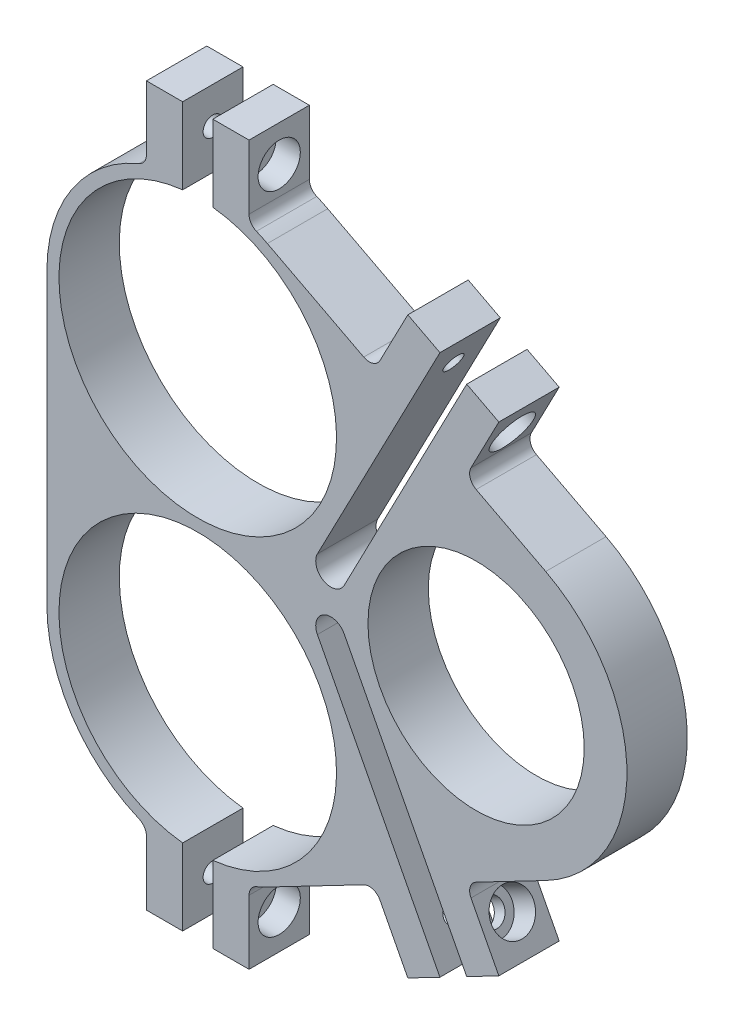
SolidWorks part; units mm, degrees
ref_plane "Front Plane" through (0, 0, 0) normal (0, 0, 1) x (1, 0, 0)
ref_plane "Top Plane" through (0, 0, 0) normal (0, 1, 0) x (1, 0, 0)
ref_plane "Right Plane" through (0, 0, 0) normal (1, 0, 0) x (0, 0, -1)
sketch "Sketch1" plane through (0, 0, 0) normal (0, 0, 1) x (1, 0, 0)
  line L0 (-39.6875, 76.2) -> (-39.6875, 0)
  line L1 (-39.6875, 38.1) -> (73.2318, 38.1) construction
  line L2 (18.3173, 111.4076) -> (46.4834, 96.7537)
  line L3 (3.9688, -36.2962) -> (3.9688, -56.3731)
  line L4 (0, 76.2) -> (0, 0) construction
  line L5 (-13.4938, -37.3231) -> (-13.4938, -56.3731)
  line L6 (3.9688, -56.3731) -> (13.4938, -56.3731)
  line L7 (-3.9688, -56.3731) -> (-13.4938, -56.3731)
  line L8 (13.4938, -37.3231) -> (13.4938, -56.3731)
  line L9 (-3.9687, -36.2962) -> (-3.9688, -56.3731)
  line L10 (18.3173, -35.2076) -> (46.4834, -20.5537)
  line L11 (13.4938, 113.5231) -> (13.4938, 132.5731)
  line L12 (-3.9688, 132.5731) -> (-13.4938, 132.5731)
  line L13 (3.9688, 132.5731) -> (13.4938, 132.5731)
  line L14 (3.9688, 132.5731) -> (3.9688, 112.4962)
  line L15 (-13.4938, 113.5231) -> (-13.4938, 132.5731)
  line L16 (54.9332, 92.3576) -> (61.9747, 88.6941) construction
  line L17 (54.9332, 92.3576) -> (31.487, 47.2919)
  line L18 (-3.9688, 132.5731) -> (-3.9688, 112.4962)
  line L19 (61.9747, 88.6941) -> (38.5286, 43.6284)
  line L20 (31.487, 47.2919) -> (38.5286, 43.6284) construction
  line L21 (54.9332, -16.1576) -> (31.487, 28.9081)
  line L22 (54.9332, 92.3576) -> (63.7255, 109.2572)
  line L23 (3.9688, 132.5731) -> (-3.9688, 132.5731) construction
  line L24 (46.4834, 96.7537) -> (55.2757, 113.6534)
  line L25 (3.9688, -56.3731) -> (-3.9688, -56.3731) construction
  line L26 (63.7255, 109.2572) -> (55.2757, 113.6534)
  line L27 (35.0078, 45.4601) -> (58.454, 90.5259) construction
  line L28 (61.9747, 88.6941) -> (70.767, 105.5938)
  line L29 (70.767, 105.5938) -> (79.2168, 101.1976)
  line L30 (70.4245, 84.298) -> (79.2168, 101.1976)
  line L31 (70.4245, 84.298) -> (91.5491, 73.3076)
  line L32 (61.9747, -12.4941) -> (38.5286, 32.5716)
  line L33 (70.4245, -8.098) -> (79.2168, -24.9976)
  line L34 (70.767, -29.3938) -> (79.2168, -24.9976)
  line L35 (61.9747, -12.4941) -> (70.767, -29.3938)
  line L36 (54.9332, -16.1576) -> (63.7255, -33.0572)
  line L37 (63.7255, -33.0572) -> (55.2757, -37.4534)
  line L38 (46.4834, -20.5537) -> (55.2757, -37.4534)
  line L39 (35.0078, 30.7399) -> (58.454, -14.3259) construction
  line L40 (54.9332, -16.1576) -> (61.9747, -12.4941) construction
  line L41 (70.4245, -8.098) -> (91.5491, 2.8924)
  arc A0 (3.9688, -36.2962) -> (-3.9687, -36.2962) centre (0, 0) ccw
  arc A1 (-3.9688, 112.4962) -> (3.9688, 112.4962) centre (0, 76.2) ccw
  arc A2 (13.4938, 113.5231) -> (18.3173, 111.4076) centre (0, 76.2) cw
  arc A3 (-39.6875, 0) -> (-13.4938, -37.3231) centre (0, 0) ccw
  circle A4 centre (73.2318, 38.1) radius 28.448
  arc A5 (13.4938, -37.3231) -> (18.3173, -35.2076) centre (0, 0) ccw
  arc A6 (-39.6875, 76.2) -> (-13.4938, 113.5231) centre (0, 76.2) cw
  circle A7 centre (73.2318, 38.1) radius 39.6875 construction
  circle A8 centre (0, 0) radius 36.5125 construction
  circle A9 centre (0, 76.2) radius 36.5125 construction
  circle A10 centre (0, 0) radius 39.6875 construction
  circle A11 centre (73.2318, 38.1) radius 36.5125 construction
  circle A12 centre (0, 76.2) radius 39.6875 construction
  arc A13 (91.5491, 73.3076) -> (91.5491, 2.8924) centre (73.2318, 38.1) cw
  circle A14 centre (35.0078, 45.4601) radius 3.9687 construction
  arc A15 (31.487, 47.2919) -> (38.5286, 43.6284) centre (35.0078, 45.4601) ccw
  circle A16 centre (35.0078, 30.7399) radius 3.9687 construction
  arc A17 (31.487, 28.9081) -> (38.5286, 32.5716) centre (35.0078, 30.7399) cw
  point P14 (0, 36.5125)
  point P51 (58.454, 90.5259)
  point P52 (0, 0)
  point P53 (0, 0)
  dimension "D2" = 56.896
  dimension "D4" = 73.025
  dimension "D5" = 73.025
  dimension "D7" = 79.375
  dimension "D9" = 79.375
  dimension "D10" = 73.025
  dimension "D11" = 7.9375
  dimension "D1" = 7.9375
  dimension "D3" = 76.2
  dimension "D6" = 9.525
  dimension "D8" = 19.05
  dimension "D12" = 82.55
  dimension "D13" = 41.275
  dimension "D14" = 50.8
  dimension "D15" = 19.05
  dimension "D16" = 9.525
extrude "Extrude1" add sketch "Sketch1" along normal mid plane 15.875
hole_wizard "CBORE for 1/4 Socket Head Cap Screw1" positions "Sketch3" profile "Sketch2" counterbore size "1/4" standard "Ansi Inch"
sketch "Sketch3" plane through (13.4938, 0, 0) normal (1, 0, 0) x (0, 0, -1)
  line L0 (7.9375, 132.5731) -> (-7.9375, 113.5231) construction
  point P0 (0, 123.0481)
sketch "Sketch2" plane through (13.4938, 123.0481, 0) normal (0, 1, 0) x (0, 0, -1)
  line L0 (0, 0) -> (0, 9.525)
  line L1 (0, 9.525) -> (3.3782, 9.525)
  line L3 (3.3782, 9.525) -> (3.3782, 6.35)
  line L4 (3.3782, 6.35) -> (5.5562, 6.35)
  line L5 (5.5562, 6.35) -> (5.5562, 0)
  line L7 (5.5562, 0) -> (0, 0)
  line L11 (0, -6.35) -> (0, 107.95) construction
  dimension "Thru Hole Dia." = 6.7564
  dimension "Thru Hole Depth" = 9.525
  dimension "C'Bore Dia." = 11.1125
  dimension "C'Bore Depth" = 6.35
hole_wizard "1/4-20 Tapped Hole1" positions "Sketch5" profile "Sketch4" tap size "1/4-20" standard "Ansi Inch" end condition through all
sketch "Sketch5" plane through (-3.9687, 0, 0) normal (1, 0, 0) x (0, 0, -1)
  point P0 (0, 123.0481)
sketch "Sketch4" plane through (-3.9688, 123.0481, 0) normal (0, 1, 0) x (0, 0, -1)
  line L0 (0, 0) -> (0, 35.7188)
  line L1 (0, 35.7188) -> (2.5527, 35.7188)
  line L2 (2.5527, 35.7188) -> (2.5527, 0)
  line L5 (2.5527, 0) -> (0, 0)
  line L11 (0, -6.35) -> (0, 107.95) construction
  dimension "Thru Tap Drill Dia." = 5.1054
  dimension "Thru Tap Drill Depth" = 35.7188
cosmetic thread "Hole Thread1" parameters "D2"=6.35
hole_wizard "CBORE for 1/4 Socket Head Cap Screw3" positions "Sketch16" profile "Sketch17" counterbore size "1/4" standard "Ansi Inch"
sketch "Sketch16" plane through (13.4938, 0, 0) normal (1, 0, 0) x (0, 0, -1)
  line L0 (7.9375, -37.3231) -> (-7.9375, -56.3731) construction
  point P0 (0, -46.8481)
sketch "Sketch17" plane through (13.4938, -46.8481, 0) normal (0, 1, 0) x (0, 0, -1)
  line L0 (0, 0) -> (0, 9.525)
  line L1 (0, 9.525) -> (3.3782, 9.525)
  line L3 (3.3782, 9.525) -> (3.3782, 6.35)
  line L4 (3.3782, 6.35) -> (5.5562, 6.35)
  line L5 (5.5562, 6.35) -> (5.5562, 0)
  line L7 (5.5562, 0) -> (0, 0)
  line L11 (0, -6.35) -> (0, 107.95) construction
  dimension "Thru Hole Dia." = 6.7564
  dimension "Thru Hole Depth" = 9.525
  dimension "C'Bore Dia." = 11.1125
  dimension "C'Bore Depth" = 6.35
hole_wizard "1/4-20 Tapped Hole4" positions "Sketch19" profile "Sketch21" tap size "1/4-20" standard "Ansi Inch" end condition through all
sketch "Sketch19" plane through (-3.9687, 0, 0) normal (1, 0, 0) x (0, 0, -1)
  point P0 (0, -46.8481)
sketch "Sketch21" plane through (-3.9687, -46.8481, 0) normal (0, 1, 0) x (0, 0, -1)
  line L0 (0, 0) -> (0, 35.7188)
  line L1 (0, 35.7188) -> (2.5527, 35.7188)
  line L2 (2.5527, 35.7188) -> (2.5527, 0)
  line L5 (2.5527, 0) -> (0, 0)
  line L11 (0, -6.35) -> (0, 107.95) construction
  dimension "Thru Tap Drill Dia." = 5.1054
  dimension "Thru Tap Drill Depth" = 35.7188
cosmetic thread "Hole Thread4" parameters "D2"=6.35
sketch "Sketch29" plane through (20.9079, -10.8777, 0) normal (0.8871, -0.4615, 0) x (0, 0, -1)
  line L0 (7.9375, 126.3361) -> (-7.9375, 107.2861) construction
hole_wizard "CBORE for 1/4 Socket Head Cap Screw4" positions "Sketch30" profile "Sketch31" counterbore size "1/4" standard "ANSI Inch"
sketch "Sketch30" plane through (20.9079, -10.8777, 0) normal (0.8871, -0.4615, 0) x (0, 0, -1)
  line L0 (7.9375, 126.3361) -> (-7.9375, 107.2861) construction
  point P0 (0, 116.8111)
sketch "Sketch31" plane through (74.8207, 92.7478, 0) normal (0, 0, 1) x (0.4615, 0.8871, 0)
  line L0 (0, 0) -> (0, 9.525)
  line L1 (0, 9.525) -> (3.3782, 9.525)
  line L3 (3.3782, 9.525) -> (3.3782, 6.35)
  line L4 (3.3782, 6.35) -> (5.5562, 6.35)
  line L5 (5.5562, 6.35) -> (5.5562, 0)
  line L7 (5.5562, 0) -> (0, 0)
  line L11 (0, -6.35) -> (0, 107.95) construction
  dimension "Thru Hole Dia." = 6.7564
  dimension "Thru Hole Depth" = 9.525
  dimension "C'Bore Dia." = 11.1125
  dimension "C'Bore Depth" = 6.35
hole_wizard "1/4-20 Tapped Hole5" positions "Sketch32" profile "Sketch33" tap size "1/4-20" standard "ANSI Inch"
sketch "Sketch32" plane through (5.4166, -2.818, 0) normal (0.8871, -0.4615, 0) x (0, 0, -1)
  point P0 (0, 116.8111)
sketch "Sketch33" plane through (59.3293, 100.8074, 0) normal (0, 0, 1) x (0.4615, 0.8871, 0)
  line L0 (0, 0) -> (0, 9.525)
  line L1 (0, 9.525) -> (2.5527, 9.525)
  line L2 (2.5527, 9.525) -> (2.5527, 0)
  line L5 (2.5527, 0) -> (0, 0)
  line L11 (0, -6.35) -> (0, 107.95) construction
  dimension "Thru Tap Drill Dia." = 5.1054
  dimension "Thru Tap Drill Depth" = 9.525
cosmetic thread "Hole Thread5" parameters "D2"=6.35
sketch "Sketch34" plane through (52.1072, 27.1096, 0) normal (0.8871, 0.4615, 0) x (0, 0, -1)
  line L0 (-7.9375, -58.7375) -> (7.9375, -39.6875) construction
hole_wizard "CBORE for 1/4 Socket Head Cap Screw5" positions "Sketch35" profile "Sketch36" counterbore size "1/4" standard "ANSI Inch"
sketch "Sketch35" plane through (52.1072, 27.1096, 0) normal (0.8871, 0.4615, 0) x (0, 0, -1)
  line L0 (-7.9375, -58.7375) -> (7.9375, -39.6875) construction
  point P0 (0, -49.2125)
sketch "Sketch36" plane through (74.8207, -16.5478, 0) normal (0, 0, 1) x (-0.4615, 0.8871, 0)
  line L0 (0, 0) -> (0, 9.525)
  line L1 (0, 9.525) -> (3.3782, 9.525)
  line L3 (3.3782, 9.525) -> (3.3782, 6.35)
  line L4 (3.3782, 6.35) -> (5.5562, 6.35)
  line L5 (5.5562, 6.35) -> (5.5563, 0)
  line L7 (5.5563, 0) -> (0, 0)
  line L11 (0, -6.35) -> (0, 107.95) construction
  dimension "Thru Hole Dia." = 6.7564
  dimension "Thru Hole Depth" = 9.525
  dimension "C'Bore Dia." = 11.1125
  dimension "C'Bore Depth" = 6.35
hole_wizard "1/4-20 Tapped Hole6" positions "Sketch39" profile "Sketch40" tap size "1/4-20" standard "ANSI Inch"
sketch "Sketch39" plane through (36.6159, 19.05, 0) normal (0.8871, 0.4615, 0) x (0, 0, -1)
  point P0 (0, -49.2125)
sketch "Sketch40" plane through (59.3293, -24.6074, 0) normal (0, 0, 1) x (-0.4615, 0.8871, 0)
  line L0 (0, 0) -> (0, 9.525)
  line L1 (0, 9.525) -> (2.5527, 9.525)
  line L2 (2.5527, 9.525) -> (2.5527, 0)
  line L5 (2.5527, 0) -> (0, 0)
  line L11 (0, -6.35) -> (0, 107.95) construction
  dimension "Thru Tap Drill Dia." = 5.1054
  dimension "Thru Tap Drill Depth" = 9.525
cosmetic thread "Hole Thread6" parameters "D2"=6.35
fillet "Fillet1" radius 3.175 8 edges at (13.4938, 113.5231, 0) (-13.4938, 113.5231, 0) (-13.4938, -37.3231, 0) (13.4938, -37.3231, 0) (46.4834, -20.5537, 0) (70.4245, -8.098, 0) (46.4834, 96.7537, 0) (70.4245, 84.298, 0)
